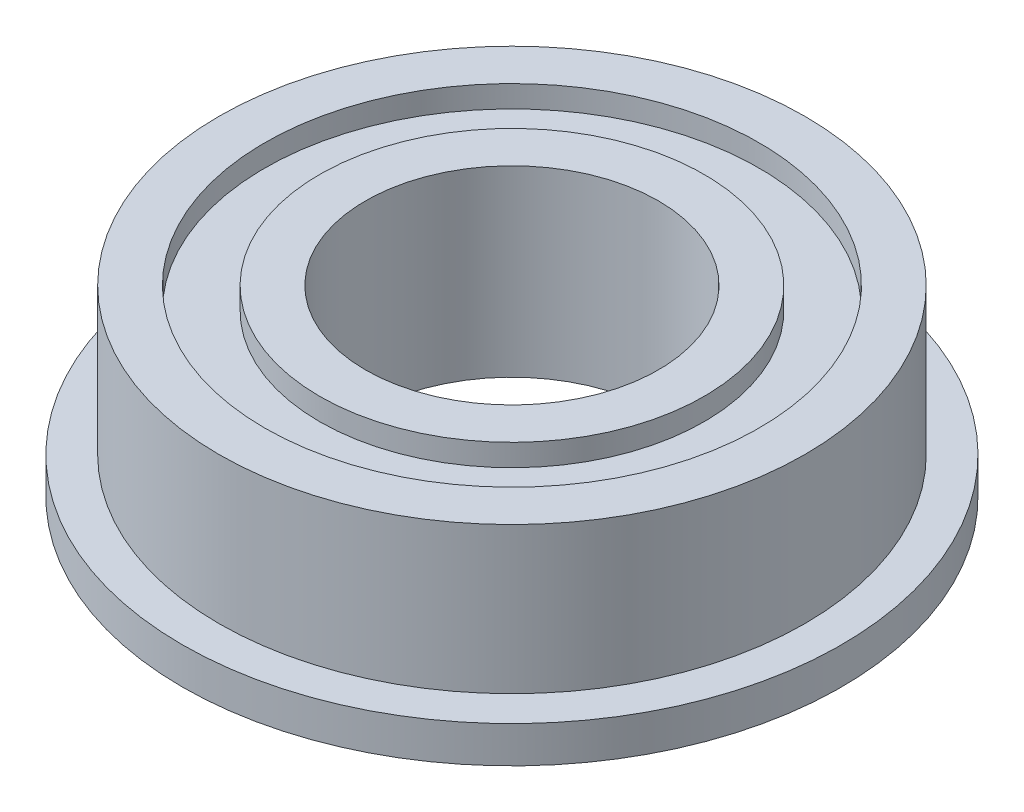
SolidWorks part; units mm, degrees
ref_plane "Front Plane" through (0, 0, 0) normal (0, 0, 1) x (1, 0, 0)
ref_plane "Top Plane" through (0, 0, 0) normal (0, 1, 0) x (1, 0, 0)
ref_plane "Right Plane" through (0, 0, 0) normal (1, 0, 0) x (0, 0, -1)
sketch "Sketch1" plane through (0, 0, 0) normal (0, 1, 0) x (1, 0, 0)
  circle A0 centre (0, 0) radius 9
  circle A1 centre (0, 0) radius 4
  dimension "D1" = 18
  dimension "D2" = 8
extrude "Boss-Extrude1" add sketch "Sketch1" along normal blind 1
sketch "Sketch2" plane through (0, 1, 0) normal (0, 1, 0) x (1, 0, 0)
  circle A0 centre (0, 0) radius 8
  circle A1 centre (0, 0) radius 4
  dimension "D1" = 16
extrude "Boss-Extrude2" add sketch "Sketch2" along normal blind 4
sketch "Sketch3" plane through (0, 5, 0) normal (0, 1, 0) x (1, 0, 0)
  circle A0 centre (0, 0) radius 5.25
  circle A1 centre (0, 0) radius 6.75
  dimension "D1" = 13.5
  dimension "D2" = 10.5
extrude "Cut-Extrude1" cut sketch "Sketch3" against normal blind 0.6
sketch "Sketch4" plane through (0, 0, 0) normal (0, -1, 0) x (-1, 0, 0)
  circle A0 centre (0, 0) radius 5.25
  circle A1 centre (0, 0) radius 6.75
  dimension "D1" = 13.5
  dimension "D2" = 10.5
extrude "Cut-Extrude2" cut sketch "Sketch4" against normal blind 0.6
